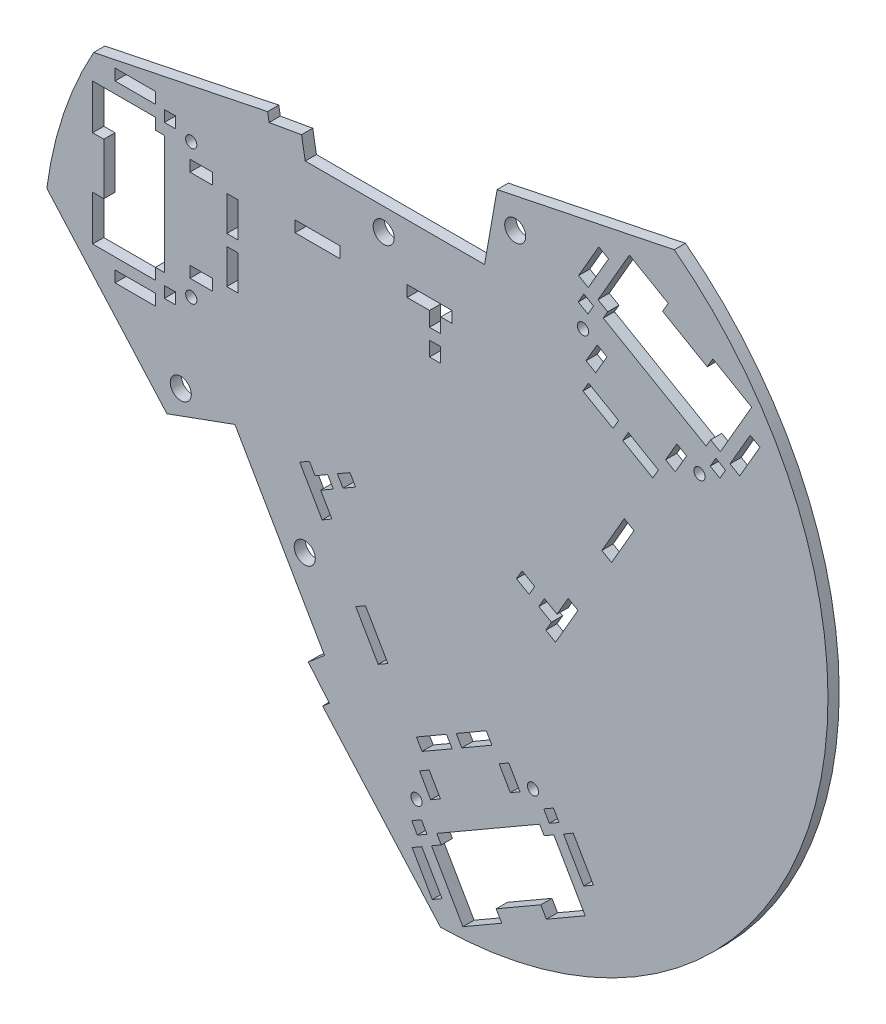
SolidWorks part; units mm, degrees
material "Balsa"
ref_plane "Plan de face" through (0, 0, 0) normal (0, 0, 1) x (1, 0, 0)
ref_plane "Plan de dessus" through (0, 0, 0) normal (0, 1, 0) x (1, 0, 0)
ref_plane "Plan de droite" through (0, 0, 0) normal (1, 0, 0) x (0, 0, -1)
sketch "Esquisse1" plane through (0, 0, 0) normal (0, 0, 1) x (1, 0, 0)
  circle A0 centre (148.0804, -12.1102) radius 175
extrude "Boss.-Extru.1" add sketch "Esquisse1" along normal blind 5
sketch "Esquisse2" plane through (0, 0, 0) normal (0, 0, -1) x (-1, 0, 0)
  line L0 (-155.3118, 53.7774) -> (-135.3118, 53.7774)
  line L1 (-150.3118, 37.2774) -> (-145.3118, 37.2774)
  line L2 (-150.3118, 37.2774) -> (-150.3118, 30.7774)
  line L3 (-150.3118, 30.7774) -> (-145.3118, 30.7774)
  line L4 (-145.3118, 37.2774) -> (-145.3118, 30.7774)
  line L5 (-105.3118, 53.7774) -> (-85.3118, 53.7774)
  line L6 (-105.3118, 53.7774) -> (-105.3118, 48.7774)
  line L7 (-105.3118, 48.7774) -> (-85.3118, 48.7774)
  line L8 (-85.3118, 53.7774) -> (-85.3118, 48.7774)
  line L9 (-59.86, 48.7774) -> (-54.86, 48.7774)
  line L10 (-59.86, 48.7774) -> (-59.86, 33.2774)
  line L11 (-59.86, 33.2774) -> (-54.86, 33.2774)
  line L12 (-54.86, 48.7774) -> (-54.86, 33.2774)
  line L13 (-59.86, 28.2774) -> (-54.86, 28.2774)
  line L14 (-59.86, 28.2774) -> (-59.86, 12.7774)
  line L15 (-59.86, 12.7774) -> (-54.86, 12.7774)
  line L16 (-54.86, 28.2774) -> (-54.86, 12.7774)
  line L17 (-48.43, 12.7774) -> (-38.43, 12.7774)
  line L18 (-48.43, 12.7774) -> (-48.43, 7.7774)
  line L19 (-48.43, 7.7774) -> (-38.43, 7.7774)
  line L20 (-38.43, 12.7774) -> (-38.43, 7.7774)
  line L21 (-32, -0.7226) -> (-27, -0.7226)
  line L22 (-32, -0.7226) -> (-32, -5.7226)
  line L23 (-32, -5.7226) -> (-27, -5.7226)
  line L24 (-27, -0.7226) -> (-27, -5.7226)
  line L25 (-23, -5.7226) -> (-5, -5.7226)
  line L26 (-23, -5.7226) -> (-23, -10.7226)
  line L27 (-23, -10.7226) -> (-5, -10.7226)
  line L28 (-5, -5.7226) -> (-5, -10.7226)
  line L29 (0, -0.7226) -> (5, -0.7226)
  line L30 (0, -0.7226) -> (0, 19.2774)
  line L31 (0, 19.2774) -> (5, 19.2774)
  line L32 (5, -0.7226) -> (5, 19.2774)
  line L33 (0, 42.2774) -> (5, 42.2774)
  line L34 (0, 42.2774) -> (0, 62.2774)
  line L35 (0, 62.2774) -> (5, 62.2774)
  line L36 (5, 42.2774) -> (5, 62.2774)
  line L37 (-23, 67.2774) -> (-5, 67.2774)
  line L38 (-23, 67.2774) -> (-23, 72.2774)
  line L39 (-23, 72.2774) -> (-5, 72.2774)
  line L40 (-5, 67.2774) -> (-5, 72.2774)
  line L41 (-27, 67.2774) -> (-32, 67.2774)
  line L42 (-27, 67.2774) -> (-27, 62.2774)
  line L43 (-27, 62.2774) -> (-32, 62.2774)
  line L44 (-32, 67.2774) -> (-32, 62.2774)
  line L45 (-38.43, 53.7774) -> (-48.43, 53.7774)
  line L46 (-38.43, 53.7774) -> (-38.43, 48.7774)
  line L47 (-38.43, 48.7774) -> (-48.43, 48.7774)
  line L48 (-48.43, 53.7774) -> (-48.43, 48.7774)
  line L49 (-135.3118, 53.7774) -> (-135.3118, 48.7774)
  line L50 (-135.3118, 48.7774) -> (-145.3118, 48.7774)
  line L51 (-135.3118, 48.7774) -> (-155.3118, 48.7774) construction
  line L52 (-145.3118, 48.7774) -> (-145.3118, 42.2774)
  line L53 (-145.3118, 42.2774) -> (-150.3118, 42.2774)
  line L54 (-150.3118, 42.2774) -> (-150.3118, 48.7774)
  line L55 (-150.3118, 48.7774) -> (-155.3118, 48.7774)
  line L56 (-155.3118, 48.7774) -> (-155.3118, 53.7774)
  line L57 (-87.4044, -38.7914) -> (-97.4044, -56.1119)
  line L58 (-104.1938, -34.8716) -> (-106.6938, -39.2017)
  line L59 (-104.1938, -34.8716) -> (-109.823, -31.6216)
  line L60 (-109.823, -31.6216) -> (-112.323, -35.9517)
  line L61 (-106.6938, -39.2017) -> (-112.323, -35.9517)
  line L62 (-112.4044, -82.0927) -> (-122.4044, -99.4132)
  line L63 (-112.4044, -82.0927) -> (-116.7345, -79.5927)
  line L64 (-116.7345, -79.5927) -> (-126.7345, -96.9132)
  line L65 (-122.4044, -99.4132) -> (-126.7345, -96.9132)
  line L66 (-139.4604, -118.9551) -> (-141.9604, -123.2852)
  line L67 (-139.4604, -118.9551) -> (-152.8838, -111.2051)
  line L68 (-152.8838, -111.2051) -> (-155.3838, -115.5352)
  line L69 (-141.9604, -123.2852) -> (-155.3838, -115.5352)
  line L70 (-157.2139, -108.7051) -> (-159.7139, -113.0352)
  line L71 (-157.2139, -108.7051) -> (-170.6373, -100.9551)
  line L72 (-170.6373, -100.9551) -> (-173.1373, -105.2852)
  line L73 (-159.7139, -113.0352) -> (-173.1373, -105.2852)
  line L74 (-176.3523, -110.8538) -> (-181.3523, -119.514)
  line L75 (-176.3523, -110.8538) -> (-180.6825, -108.3538)
  line L76 (-180.6825, -108.3538) -> (-185.6825, -117.014)
  line L77 (-181.3523, -119.514) -> (-185.6825, -117.014)
  line L78 (-196.2587, -118.3326) -> (-198.7587, -122.6627)
  line L79 (-196.2587, -118.3326) -> (-200.5888, -115.8326)
  line L80 (-200.5888, -115.8326) -> (-203.0888, -120.1627)
  line L81 (-198.7587, -122.6627) -> (-203.0888, -120.1627)
  line L82 (-205.0888, -123.6268) -> (-214.0888, -139.2153)
  line L83 (-205.0888, -123.6268) -> (-209.4189, -121.1268)
  line L84 (-209.4189, -121.1268) -> (-218.4189, -136.7153)
  line L85 (-214.0888, -139.2153) -> (-218.4189, -136.7153)
  line L86 (-212.2587, -146.0454) -> (-214.7587, -150.3755)
  line L87 (-212.2587, -146.0454) -> (-194.9382, -156.0454)
  line L88 (-194.9382, -156.0454) -> (-197.4382, -160.3755)
  line L89 (-214.7587, -150.3755) -> (-197.4382, -160.3755)
  line L90 (-175.0196, -167.5454) -> (-177.5196, -171.8755)
  line L91 (-175.0196, -167.5454) -> (-157.6991, -177.5454)
  line L92 (-157.6991, -177.5454) -> (-160.1991, -181.8755)
  line L93 (-177.5196, -171.8755) -> (-160.1991, -181.8755)
  line L94 (-141.869, -160.1268) -> (-150.869, -175.7153)
  line L95 (-141.869, -160.1268) -> (-137.5388, -162.6268)
  line L96 (-137.5388, -162.6268) -> (-146.5388, -178.2153)
  line L97 (-150.869, -175.7153) -> (-146.5388, -178.2153)
  line L98 (-139.869, -156.6627) -> (-137.369, -152.3326)
  line L99 (-139.869, -156.6627) -> (-144.1991, -154.1627)
  line L100 (-144.1991, -154.1627) -> (-141.6991, -149.8326)
  line L101 (-137.369, -152.3326) -> (-141.6991, -149.8326)
  line L102 (-145.8453, -140.014) -> (-140.8453, -131.3538)
  line L103 (-145.8453, -140.014) -> (-150.1754, -137.514)
  line L104 (-150.1754, -137.514) -> (-145.1754, -128.8538)
  line L105 (-140.8453, -131.3538) -> (-145.1754, -128.8538)
  line L106 (-97.4044, -56.1119) -> (-101.7345, -53.6119)
  line L107 (-101.7345, -53.6119) -> (-96.7345, -44.9517)
  line L108 (-96.7345, -44.9517) -> (-102.3637, -41.7017)
  line L109 (-102.3637, -41.7017) -> (-99.8637, -37.3716)
  line L110 (-99.8637, -37.3716) -> (-94.2345, -40.6216)
  line L111 (-94.2345, -40.6216) -> (-91.7345, -36.2914)
  line L112 (-91.7345, -36.2914) -> (-87.4044, -38.7914)
  line L113 (-201.5251, -51.3165) -> (-211.5251, -33.996)
  line L114 (-189.7357, -38.7364) -> (-192.2357, -34.4063)
  line L115 (-189.7357, -38.7364) -> (-184.1065, -35.4864)
  line L116 (-184.1065, -35.4864) -> (-186.6065, -31.1563)
  line L117 (-192.2357, -34.4063) -> (-186.6065, -31.1563)
  line L118 (-226.5251, -8.0153) -> (-236.5251, 9.3053)
  line L119 (-226.5251, -8.0153) -> (-222.195, -5.5153)
  line L120 (-222.195, -5.5153) -> (-232.195, 11.8053)
  line L121 (-236.5251, 9.3053) -> (-232.195, 11.8053)
  line L122 (-244.9209, 33.8472) -> (-247.4209, 38.1773)
  line L123 (-244.9209, 33.8472) -> (-231.4975, 41.5972)
  line L124 (-231.4975, 41.5972) -> (-233.9975, 45.9273)
  line L125 (-247.4209, 38.1773) -> (-233.9975, 45.9273)
  line L126 (-227.1673, 44.0972) -> (-229.6673, 48.4273)
  line L127 (-227.1673, 44.0972) -> (-213.7439, 51.8472)
  line L128 (-213.7439, 51.8472) -> (-216.2439, 56.1773)
  line L129 (-229.6673, 48.4273) -> (-216.2439, 56.1773)
  line L130 (-219.4589, 61.7458) -> (-224.4589, 70.4061)
  line L131 (-219.4589, 61.7458) -> (-215.1288, 64.2458)
  line L132 (-215.1288, 64.2458) -> (-220.1288, 72.9061)
  line L133 (-224.4589, 70.4061) -> (-220.1288, 72.9061)
  line L134 (-215.9826, 82.7246) -> (-218.4826, 87.0547)
  line L135 (-215.9826, 82.7246) -> (-211.6525, 85.2246)
  line L136 (-211.6525, 85.2246) -> (-214.1525, 89.5547)
  line L137 (-218.4826, 87.0547) -> (-214.1525, 89.5547)
  line L138 (-216.1525, 93.0188) -> (-225.1525, 108.6073)
  line L139 (-216.1525, 93.0188) -> (-211.8223, 95.5188)
  line L140 (-211.8223, 95.5188) -> (-220.8223, 111.1073)
  line L141 (-225.1525, 108.6073) -> (-220.8223, 111.1073)
  line L142 (-231.9826, 110.4374) -> (-234.4826, 114.7676)
  line L143 (-231.9826, 110.4374) -> (-249.3031, 100.4374)
  line L144 (-249.3031, 100.4374) -> (-251.8031, 104.7676)
  line L145 (-234.4826, 114.7676) -> (-251.8031, 104.7676)
  line L146 (-269.2217, 88.9374) -> (-271.7217, 93.2676)
  line L147 (-269.2217, 88.9374) -> (-286.5422, 78.9374)
  line L148 (-286.5422, 78.9374) -> (-289.0422, 83.2676)
  line L149 (-271.7217, 93.2676) -> (-289.0422, 83.2676)
  line L150 (-279.3723, 56.5188) -> (-288.3723, 72.1073)
  line L151 (-279.3723, 56.5188) -> (-283.7025, 54.0188)
  line L152 (-283.7025, 54.0188) -> (-292.7025, 69.6073)
  line L153 (-288.3723, 72.1073) -> (-292.7025, 69.6073)
  line L154 (-277.3723, 53.0547) -> (-274.8723, 48.7246)
  line L155 (-277.3723, 53.0547) -> (-273.0422, 55.5547)
  line L156 (-273.0422, 55.5547) -> (-270.5422, 51.2246)
  line L157 (-274.8723, 48.7246) -> (-270.5422, 51.2246)
  line L158 (-259.966, 49.9061) -> (-254.966, 41.2458)
  line L159 (-259.966, 49.9061) -> (-255.6359, 52.4061)
  line L160 (-255.6359, 52.4061) -> (-250.6359, 43.7458)
  line L161 (-254.966, 41.2458) -> (-250.6359, 43.7458)
  line L162 (-211.5251, -33.996) -> (-207.195, -31.496)
  line L163 (-207.195, -31.496) -> (-202.195, -40.1563)
  line L164 (-202.195, -40.1563) -> (-196.5658, -36.9063)
  line L165 (-196.5658, -36.9063) -> (-194.0658, -41.2364)
  line L166 (-194.0658, -41.2364) -> (-199.695, -44.4864)
  line L167 (-199.695, -44.4864) -> (-197.195, -48.8165)
  line L168 (-197.195, -48.8165) -> (-201.5251, -51.3165)
  point P204 (-148.0804, -12.1102)
  dimension "D1" = 3
extrude "Enlèv. mat.-Extru.1" cut sketch "Esquisse2" against normal blind 5
sketch "Esquisse3" plane through (0, 0, 0) normal (0, 0, -1) x (-1, 0, 0)
  line L0 (-59.86, 33.2774) -> (-59.86, 28.2774) construction
  line L1 (-59.86, 30.7774) -> (32.4397, 30.7774) construction
  line L2 (0, -0.7226) -> (-23, -0.7226)
  line L3 (-23, -0.7226) -> (-23, 4.2774)
  line L4 (-23, 4.2774) -> (-27, 4.2774)
  line L5 (-23, 57.2774) -> (-27, 57.2774)
  line L6 (-23, 62.2774) -> (-23, 57.2774)
  line L7 (0, 62.2774) -> (-23, 62.2774)
  line L8 (-27, 57.2774) -> (-27, 4.2774)
  line L9 (0, -0.7226) -> (0, 62.2774)
  line L10 (-212.2587, -146.0454) -> (-200.7587, -126.1268)
  line L11 (-200.7587, -126.1268) -> (-196.4286, -128.6268)
  line L12 (-196.4286, -128.6268) -> (-194.4286, -125.1627)
  line L13 (-150.5292, -155.1268) -> (-148.5292, -151.6627)
  line L14 (-146.1991, -157.6268) -> (-150.5292, -155.1268)
  line L15 (-157.6991, -177.5454) -> (-146.1991, -157.6268)
  line L16 (-148.5292, -151.6627) -> (-194.4286, -125.1627)
  line L17 (-212.2587, -146.0454) -> (-157.6991, -177.5454)
  line L18 (-152.8838, -111.2051) -> (-157.2139, -108.7051) construction
  line L19 (-155.0489, -109.9551) -> (-201.1987, -189.889) construction
  line L20 (-231.9826, 110.4374) -> (-220.4826, 90.5188)
  line L21 (-220.4826, 90.5188) -> (-224.8127, 88.0188)
  line L22 (-224.8127, 88.0188) -> (-222.8127, 84.5547)
  line L23 (-270.7121, 61.5188) -> (-268.7121, 58.0547)
  line L24 (-275.0422, 59.0188) -> (-270.7121, 61.5188)
  line L25 (-286.5422, 78.9374) -> (-275.0422, 59.0188)
  line L26 (-268.7121, 58.0547) -> (-222.8127, 84.5547)
  line L27 (-231.9826, 110.4374) -> (-286.5422, 78.9374)
  line L28 (-231.4975, 41.5972) -> (-227.1673, 44.0972) construction
  line L29 (-229.3324, 42.8472) -> (-275.4822, 122.781) construction
  point P42 (-148.0804, -12.1102)
  dimension "D1" = 5
  dimension "D2" = 4
  dimension "D3" = 23
  dimension "D4" = 3
extrude "Enlèv. mat.-Extru.2" cut sketch "Esquisse3" against normal blind 5
sketch "Esquisse4" plane through (0, 0, 0) normal (0, 0, -1) x (-1, 0, 0)
  line L0 (-32, 67.2774) -> (-32, 62.2774) construction
  line L1 (-38.43, 53.7774) -> (-48.43, 53.7774) construction
  line L2 (-27, 30.7774) -> (-93.5454, 30.7774) construction
  line L3 (-27, 57.2774) -> (-27, 4.2774) construction
  line L4 (-171.4789, -138.4127) -> (-138.2062, -80.7827) construction
  line L5 (-245.7624, 71.3047) -> (-212.4897, 13.6748) construction
  circle A0 centre (-39, 60.7774) radius 2.5
  circle A1 centre (-39, 0.7774) radius 2.5
  circle A2 centre (-139.4981, -143.0204) radius 2.5
  circle A3 centre (-191.4596, -113.0204) radius 2.5
  circle A4 centre (-265.7432, 45.9124) radius 2.5
  circle A5 centre (-213.7816, 75.9124) radius 2.5
  point P27 (-148.0804, -12.1102)
  dimension "D1" = 7
  dimension "D2" = 7
  dimension "D3" = 3
extrude "Enlèv. mat.-Extru.3" cut sketch "Esquisse4" against normal blind 5
sketch "Esquisse5" plane through (0, 0, 0) normal (0, 0, -1) x (-1, 0, 0)
  line L0 (14.5132, 71.4723) -> (-73.0596, 89.4898)
  line L1 (-310.6994, 138.3825) -> (-285.7872, 259.4664)
  line L2 (-285.7872, 259.4664) -> (39.4253, 192.5562)
  line L3 (39.4253, 192.5562) -> (14.5132, 71.4723)
  line L4 (-73.0596, 89.4898) -> (-73.7478, 85.5865)
  line L5 (-175.4639, 110.5588) -> (-310.6994, 138.3825)
  line L6 (-89.86, 78.7774) -> (-169.86, 78.7774)
  line L7 (-169.86, 78.7774) -> (-175.4639, 110.5588)
  line L8 (-73.7478, 85.5865) -> (-88.2097, 88.1365)
  line L9 (-88.2097, 88.1365) -> (-89.86, 78.7774)
  line L10 (-156.9927, -194.7116) -> (-97.6027, -127.8801)
  line L11 (63.5596, 53.4756) -> (155.9652, -28.6409)
  line L12 (26.9196, -12.1102) -> (-148.0804, -12.1102) construction
  line L13 (155.9652, -28.6409) -> (-64.5871, -276.8281)
  line L14 (-64.5871, -276.8281) -> (-156.9927, -194.7116)
  line L15 (-97.6027, -127.8801) -> (-100.6389, -125.3324)
  line L16 (-28.1543, -49.7299) -> (63.5596, 53.4756)
  line L17 (-98.4797, -107.9743) -> (-58.4797, -38.6923)
  line L18 (-58.4797, -38.6923) -> (-28.1543, -49.7299)
  line L19 (-100.6389, -125.3324) -> (-91.1996, -114.0831)
  line L20 (-91.1996, -114.0831) -> (-98.4797, -107.9743)
  circle A0 centre (-183.5408, 98.7774) radius 4.7
  circle A1 centre (-124.86, 68.7774) radius 4.7
  circle A2 centre (-34.3187, -36.8444) radius 4.7
  circle A3 centre (-89.6399, -72.6635) radius 4.7
  point P15 (-148.0804, -12.1102)
  point P35 (-148.0804, -12.1102)
  dimension "D2" = 9.4
  dimension "D3" = 9.4
  dimension "D4" = 100
  dimension "D5" = 100
  dimension "D6" = 14.685
  dimension "D7" = 3.9635
  dimension "D8" = 9.5035
  dimension "D9" = 80
  dimension "D10" = 35
  dimension "D11" = 80.8876
  dimension "D12" = 58.6808
  dimension "D13" = 30
  dimension "D14" = 10
  dimension "D15" = 11.626
  dimension "D16" = 23.2204
  dimension "D17" = 2
extrude "Enlèv. mat.-Extru.4" cut sketch "Esquisse5" against normal blind 5
